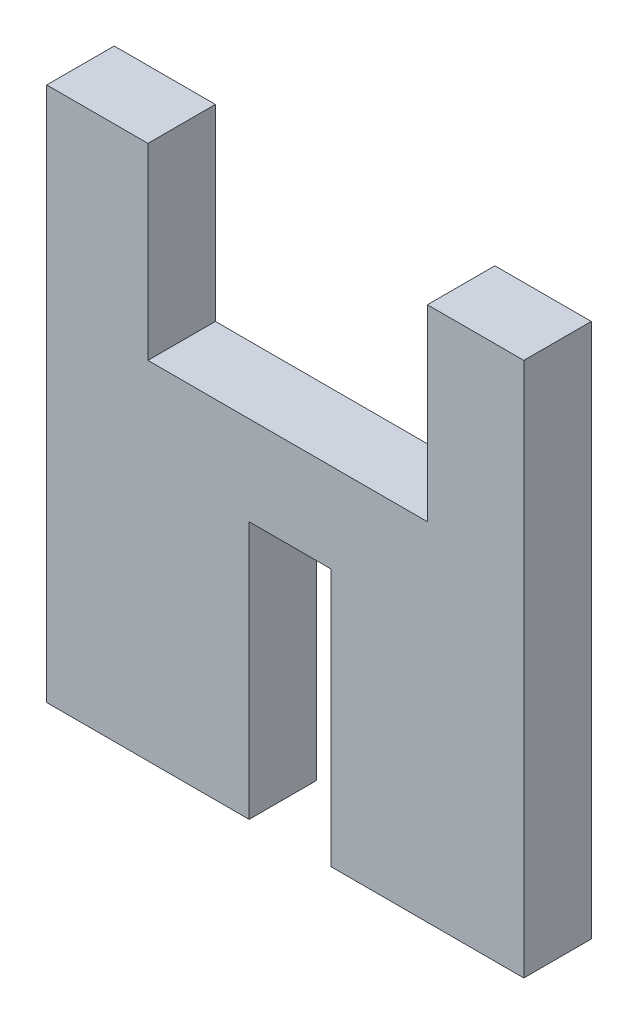
SolidWorks part; units mm, degrees
ref_plane "前视基准面" through (0, 0, 0) normal (0, 0, 1) x (1, 0, 0)
ref_plane "上视基准面" through (0, 0, 0) normal (0, 1, 0) x (1, 0, 0)
ref_plane "右视基准面" through (0, 0, 0) normal (1, 0, 0) x (0, 0, -1)
sketch "草图1" plane through (0, 0, 0) normal (0, 0, 1) x (1, 0, 0)
  line L0 (-14.3286, 13.9643) -> (-14.3286, -12.9929)
  line L1 (-14.3286, -12.9929) -> (-4.1286, -12.9929)
  line L2 (-4.1286, -12.9929) -> (-4.1286, 0)
  line L3 (-4.1286, 0) -> (0, 0)
  line L4 (0, 0) -> (0, -12.9929)
  line L5 (0, -12.9929) -> (9.7143, -12.9929)
  line L6 (9.7143, -12.9929) -> (9.7143, 13.9643)
  line L7 (9.7143, 13.9643) -> (4.8571, 13.9643)
  line L8 (4.8571, 13.9643) -> (4.8571, 4.4929)
  line L9 (4.8571, 4.4929) -> (-9.2286, 4.4929)
  line L10 (-9.2286, 4.4929) -> (-9.2286, 13.9643)
  line L11 (-9.2286, 13.9643) -> (-14.3286, 13.9643)
extrude "凸台-拉伸1" add sketch "草图1" along normal blind 3.4
